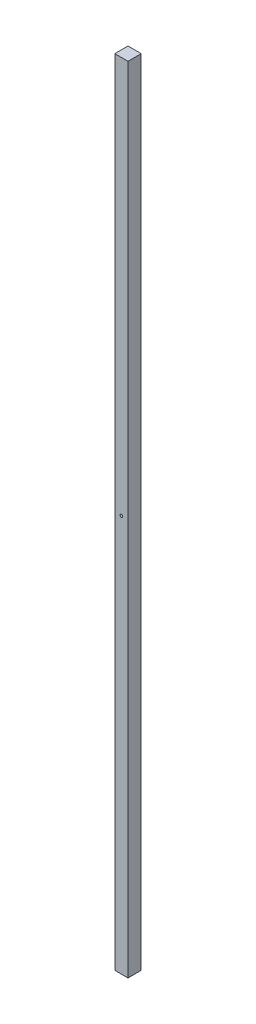
SolidWorks part; units mm, degrees
ref_plane "Спереди" through (0, 0, 0) normal (0, 0, 1) x (1, 0, 0)
ref_plane "Сверху" through (0, 0, 0) normal (0, 1, 0) x (1, 0, 0)
ref_plane "Справа" through (0, 0, 0) normal (1, 0, 0) x (0, 0, -1)
other "Configuration Table"
sketch "Эскиз1" plane through (0, 0, 0) normal (0, 1, 0) x (1, 0, 0)
  line L1 (25, 25) -> (-25, 25)
  line L2 (25, 25) -> (25, -25)
  line L3 (25, -25) -> (-25, -25)
  line L4 (-25, 25) -> (-25, -25)
  line L5 (25, 25) -> (-25, -25) construction
  line L6 (25, -25) -> (-25, 25) construction
  point P0 (0, 0)
extrude "Бобышка-Вытянуть1" add sketch "Эскиз1" along normal blind 3000
sketch "Эскиз2" plane through (0, 0, 25) normal (0, 0, 1) x (1, 0, 0)
  line L0 (0, 3000) -> (0, 0) construction
  line L1 (-25, 3000) -> (25, 3000) construction
  circle A0 centre (0, 1500) radius 5
extrude "Вырез-Вытянуть1" cut sketch "Эскиз2" against normal blind 50
